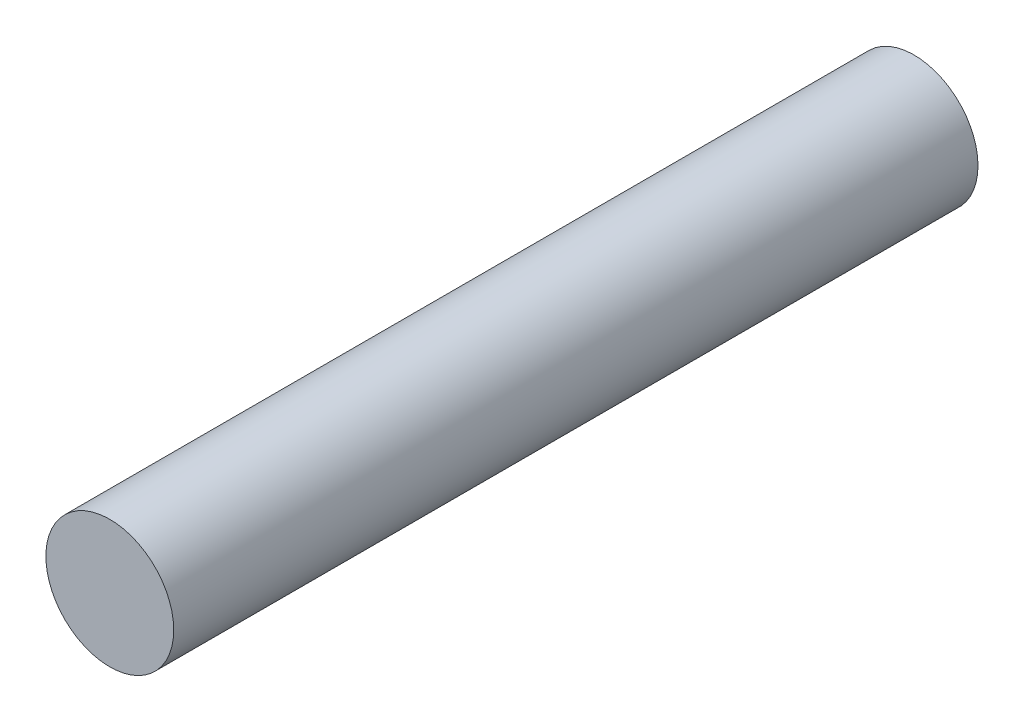
SolidWorks part; units mm, degrees
ref_plane "Front Plane" through (0, 0, 0) normal (0, 0, 1) x (1, 0, 0)
ref_plane "Top Plane" through (0, 0, 0) normal (0, 1, 0) x (1, 0, 0)
ref_plane "Right Plane" through (0, 0, 0) normal (1, 0, 0) x (0, 0, -1)
sketch "Sketch2" plane through (0, 0, 0) normal (0, 0, 1) x (1, 0, 0)
  circle A0 centre (0, 0) radius 119.2122
extrude "Boss-Extrude1" add sketch "Sketch2" along normal blind 1500
